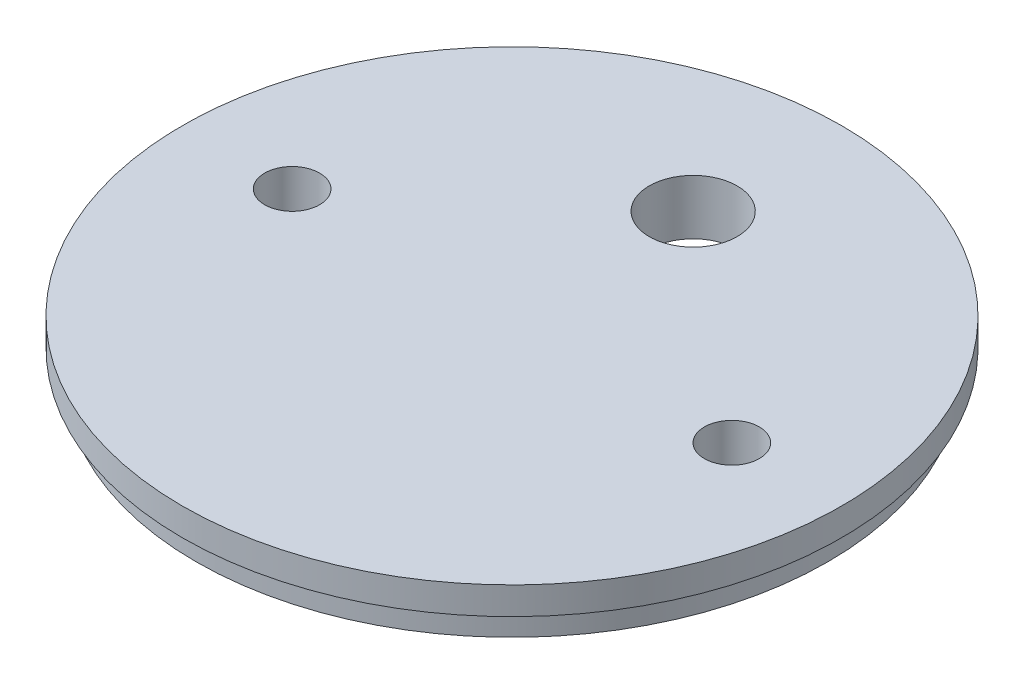
SolidWorks part; units mm, degrees
ref_plane "Front Plane" through (0, 0, 0) normal (0, 0, 1) x (1, 0, 0)
ref_plane "Top Plane" through (0, 0, 0) normal (0, 1, 0) x (1, 0, 0)
ref_plane "Right Plane" through (0, 0, 0) normal (1, 0, 0) x (0, 0, -1)
sketch "Sketch1" plane through (0, 0, 0) normal (0, 1, 0) x (1, 0, 0)
  circle A0 centre (0, 0) radius 36.5125
  dimension "D1" = 73.025
extrude "Boss-Extrude1" add sketch "Sketch1" along normal blind 3.175
sketch "Sketch2" plane through (0, 3.175, 0) normal (0, 1, 0) x (1, 0, 0)
  circle A0 centre (0, 0) radius 38.0746
  dimension "D1" = 76.1492
extrude "Boss-Extrude2" add sketch "Sketch2" along normal blind 3.175
sketch "Sketch3" plane through (0, 0, 0) normal (0, -1, 0) x (1, 0, 0)
  circle A0 centre (0, -20.9296) radius 13.97 construction
  circle A1 centre (0, 0) radius 36.5125 construction
  circle A2 centre (0, 0) radius 36.5125 construction
  circle A3 centre (0, -20.9296) radius 5.08
  circle A4 centre (0, 0) radius 38.0746 construction
  point P2 (0, -36.5125)
  point P4 (0, -34.8996)
  point P5 (0, -38.0746)
  dimension "D1" = 27.94
  dimension "D3" = 10.16
  dimension "D2" = 3.175
extrude "Cut-Extrude1" cut sketch "Sketch3" against normal through all
sketch "Sketch4" [suppressed] plane through (0, 0, 0) normal (0, -1, 0) x (1, 0, 0)
  circle A2 centre (0, -20.9296) radius 5.08 construction
  circle A3 centre (0, 7.0104) radius 16.51 construction
  circle A4 centre (0, -20.9296) radius 13.97 construction
  circle A5 centre (0, 7.0104) radius 11.43
  circle A6 centre (-15.494, 22.5044) radius 1.4999
  circle A7 centre (15.494, 22.5044) radius 1.4999
  circle A8 centre (15.494, -8.4836) radius 1.4999
  circle A9 centre (-15.494, -8.4836) radius 1.4999
  circle A10 centre (0, 0) radius 36.5125 construction
  circle A11 centre (0, 0) radius 36.5125 construction
  point P16 (0, 23.5204)
  point P17 (0, 36.5125)
  dimension "D1" = 22.86
  dimension "D2" = 2.9997
  dimension "D3" = 33.02
  dimension "D4" = 27.94
  dimension "D5" = 30.988
  dimension "D6" = 27.94
  dimension "D7" = 30.988
  dimension "D8" = 15.494
  dimension "D9" = 15.494
extrude "Cut-Extrude2" [suppressed] cut sketch "Sketch4" against normal through all
sketch "Sketch5" [suppressed] plane through (0, 0, 0) normal (0, -1, 0) x (1, 0, 0)
  circle A0 centre (0, -20.6375) radius 13.97
  circle A1 centre (0, 7.3025) radius 16.51
  circle A2 centre (0, -20.6375) radius 5.08 construction
  dimension "D1" = 27.94
  dimension "D2" = 33.02
  dimension "D3" = 27.94
sketch "Sketch6" [suppressed] plane through (0, 0, 0) normal (0, -1, 0) x (1, 0, 0)
  circle A0 centre (-25.4, 0) radius 3.175
  circle A1 centre (25.4, 0) radius 3.175
  dimension "D1" = 50.8
  dimension "D3" = 6.35
  dimension "D2" = 25.4
extrude "Cut-Extrude3" [suppressed] cut sketch "Sketch6" against normal through all
sketch "Sketch7" plane through (0, 6.35, 0) normal (0, 1, 0) x (1, 0, 0)
  circle A0 centre (-25.4, 0) radius 3.175
  circle A1 centre (25.4, 0) radius 3.175
  dimension "D1" = 6.35
  dimension "D2" = 25.4
  dimension "D3" = 50.8
extrude "Cut-Extrude4" cut sketch "Sketch7" against normal through all
sketch "Sketch8" [suppressed] plane through (0, 0, 0) normal (0, -1, 0) x (1, 0, 0)
  line L0 (-38.0746, 0) -> (-36.5125, 0)
  line L1 (38.0746, 0) -> (36.5125, 0)
  circle A0 centre (0, -20.9296) radius 8.5344
  arc A1 (-38.0746, 0) -> (38.0746, 0) centre (0, 0) ccw
  arc A2 (-36.5125, 0) -> (36.5125, 0) centre (0, 0) ccw
  dimension "D1" = 17.0688
  dimension "D2" = 76.1492
  dimension "D3" = 73.025
extrude "Cut-Extrude5" [suppressed] cut sketch "Sketch8" against normal through all
sketch "Sketch9" [suppressed] plane through (0, 0, 0) normal (0, -1, 0) x (1, 0, 0)
  circle A0 centre (-25.4, 0) radius 3.175
  circle A1 centre (25.4, 0) radius 3.175
extrude "Boss-Extrude3" [suppressed] add sketch "Sketch9" against normal up to surface (6.35 mm away)
sketch "Sketch10" [suppressed] plane through (0, 0, 0) normal (0, -1, 0) x (1, 0, 0)
  circle A0 centre (-25.4, 7.62) radius 3.175
  circle A1 centre (25.4, 7.62) radius 3.175
  dimension "D1" = 6.35
  dimension "D2" = 6.35
  dimension "D3" = 50.8
  dimension "D4" = 25.4
  dimension "D5" = 7.62
extrude "Cut-Extrude6" [suppressed] cut sketch "Sketch10" against normal through all
sketch "Sketch11" [suppressed] plane through (0, 6.35, 0) normal (0, 1, 0) x (1, 0, 0)
  circle A0 centre (-25.4, 0) radius 3.175
  circle A1 centre (25.4, 0) radius 3.175
extrude "Boss-Extrude4" [suppressed] add sketch "Sketch11" against normal up to surface (6.35 mm away)
sketch "Sketch12" [suppressed] plane through (0, 6.35, 0) normal (0, 1, 0) x (1, 0, 0)
  circle A0 centre (-25.4, -7.62) radius 3.175
  circle A1 centre (25.4, -7.62) radius 3.175
  dimension "D1" = 6.35
  dimension "D2" = 6.35
  dimension "D3" = 50.8
  dimension "D4" = 25.4
  dimension "D5" = 7.62
extrude "Cut-Extrude7" [suppressed] cut sketch "Sketch12" against normal through all
